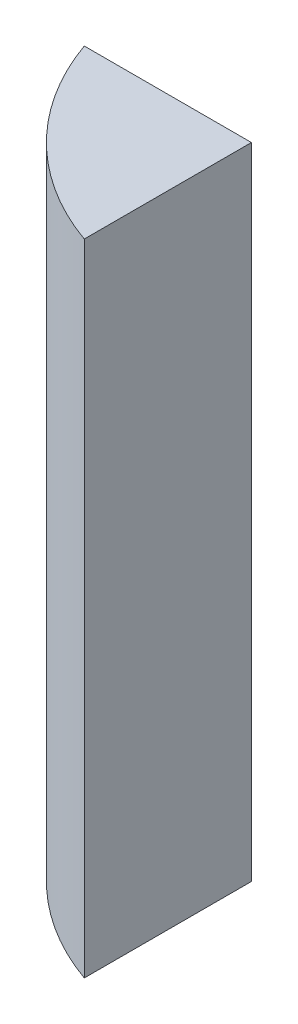
SolidWorks part; units mm, degrees
ref_plane "前视基准面" through (0, 0, 0) normal (0, 0, 1) x (1, 0, 0)
ref_plane "上视基准面" through (0, 0, 0) normal (0, 1, 0) x (1, 0, 0)
ref_plane "右视基准面" through (0, 0, 0) normal (1, 0, 0) x (0, 0, -1)
sketch "草图1" plane through (0, 0, 0) normal (0, 1, 0) x (1, 0, 0)
  line L0 (-56.5685, -20) -> (56.5685, -20)
  line L1 (-56.5685, 20) -> (56.5685, 20)
  line L2 (-20, 56.5685) -> (-20, -56.5685)
  line L3 (20, 56.5685) -> (20, -56.5685)
  circle A0 centre (0, 0) radius 60
  dimension "D1" = 120
  dimension "D2" = 20
  dimension "D3" = 20
  dimension "D4" = 20
  dimension "D5" = 20
extrude "凸台-拉伸1" add sketch "草图1" along normal blind 140 contours L0 A0 L2
